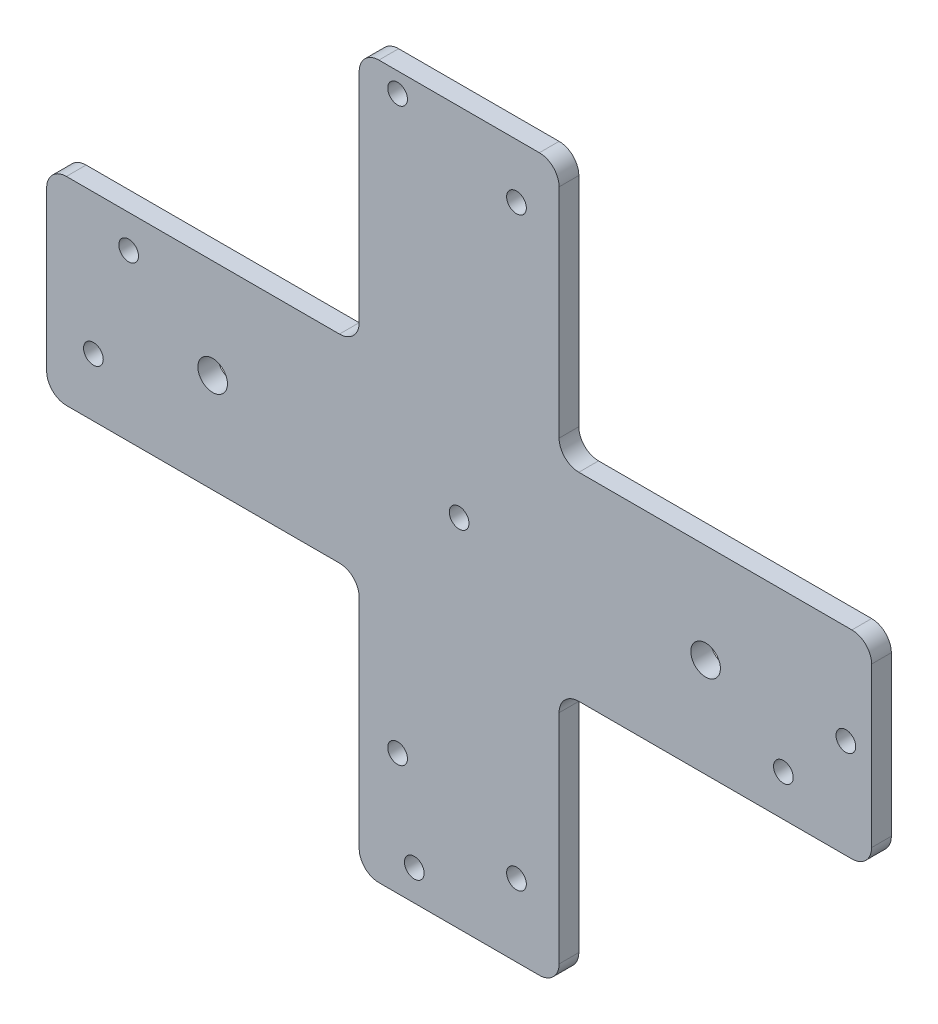
SolidWorks part; units mm, degrees
ref_plane "前视基准面" through (0, 0, 0) normal (0, 0, 1) x (1, 0, 0)
ref_plane "上视基准面" through (0, 0, 0) normal (0, 1, 0) x (1, 0, 0)
ref_plane "右视基准面" through (0, 0, 0) normal (1, 0, 0) x (0, 0, -1)
other "Configuration Table"
sketch "草图3" plane through (0, 0, 0) normal (0, 0, 1) x (1, 0, 0)
  line L459 (118.0628, 110.611) -> (90.3647, 110.611)
  line L528 (88.3647, 108.611) -> (88.3647, 92.4905)
  line L553 (90.3647, 90.4905) -> (118.0628, 90.4905)
  line L636 (172.0386, 92.4905) -> (172.0386, 108.611)
  line L637 (140.3405, 100.5507) -> (155.2017, 100.5507) construction
  line L638 (122.0628, 136.6792) -> (138.3405, 136.6792)
  line L641 (140.3405, 134.6792) -> (140.3405, 112.611)
  line L642 (130.2017, 136.6792) -> (130.2017, 1117.8543) construction
  line L643 (142.3405, 110.611) -> (170.0386, 110.611)
  line L644 (120.0628, 134.6792) -> (120.0628, 112.611)
  line L645 (120.0628, 66.4223) -> (120.0628, 88.4905)
  line L646 (140.3405, 66.4223) -> (140.3405, 88.4905)
  line L647 (122.0628, 64.4223) -> (138.3405, 64.4223)
  line L648 (142.3405, 90.4905) -> (170.0386, 90.4905)
  circle A1019 centre (105.2017, 100.5507) radius 1.5
  circle A1190 centre (155.2017, 100.5507) radius 1.5
  arc A1197 (170.0386, 90.4905) -> (172.0386, 92.4905) centre (170.0386, 92.4905) ccw
  arc A1199 (172.0386, 108.611) -> (170.0386, 110.611) centre (170.0386, 108.611) ccw
  arc A1201 (90.3647, 110.611) -> (88.3647, 108.611) centre (90.3647, 108.611) ccw
  arc A1203 (88.3647, 92.4905) -> (90.3647, 90.4905) centre (90.3647, 92.4905) ccw
  arc A1205 (138.3405, 136.6792) -> (140.3405, 134.6792) centre (138.3405, 134.6792) cw
  arc A1206 (140.3405, 112.611) -> (142.3405, 110.611) centre (142.3405, 112.611) ccw
  arc A1207 (120.0628, 112.611) -> (118.0628, 110.611) centre (118.0628, 112.611) cw
  arc A1208 (122.0628, 136.6792) -> (120.0628, 134.6792) centre (122.0628, 134.6792) ccw
  arc A1209 (122.0628, 64.4223) -> (120.0628, 66.4223) centre (122.0628, 66.4223) cw
  arc A1210 (120.0628, 88.4905) -> (118.0628, 90.4905) centre (118.0628, 88.4905) ccw
  arc A1211 (140.3405, 88.4905) -> (142.3405, 90.4905) centre (142.3405, 88.4905) cw
  arc A1212 (138.3405, 64.4223) -> (140.3405, 66.4223) centre (138.3405, 66.4223) ccw
  circle A1213 centre (136.0179, 131.1568) radius 1
  circle A1214 centre (123.9599, 76.7539) radius 1
  circle A1215 centre (93.1055, 96.4014) radius 1
  circle A1216 centre (169.4257, 100.5507) radius 1
  circle A1217 centre (130.2017, 100.5507) radius 1
  circle A1218 centre (125.6502, 67.534) radius 1
  circle A1219 centre (123.9599, 134.6792) radius 1
  circle A1220 centre (96.6834, 107.2631) radius 1
  circle A1221 centre (163.0894, 94.6689) radius 1
  circle A1222 centre (136.0179, 71.7702) radius 1
  point P12 (88.3647, 100.5507)
  point P15 (172.0386, 100.5507)
extrude "凸台-拉伸1" add sketch "草图3" along normal blind 2
